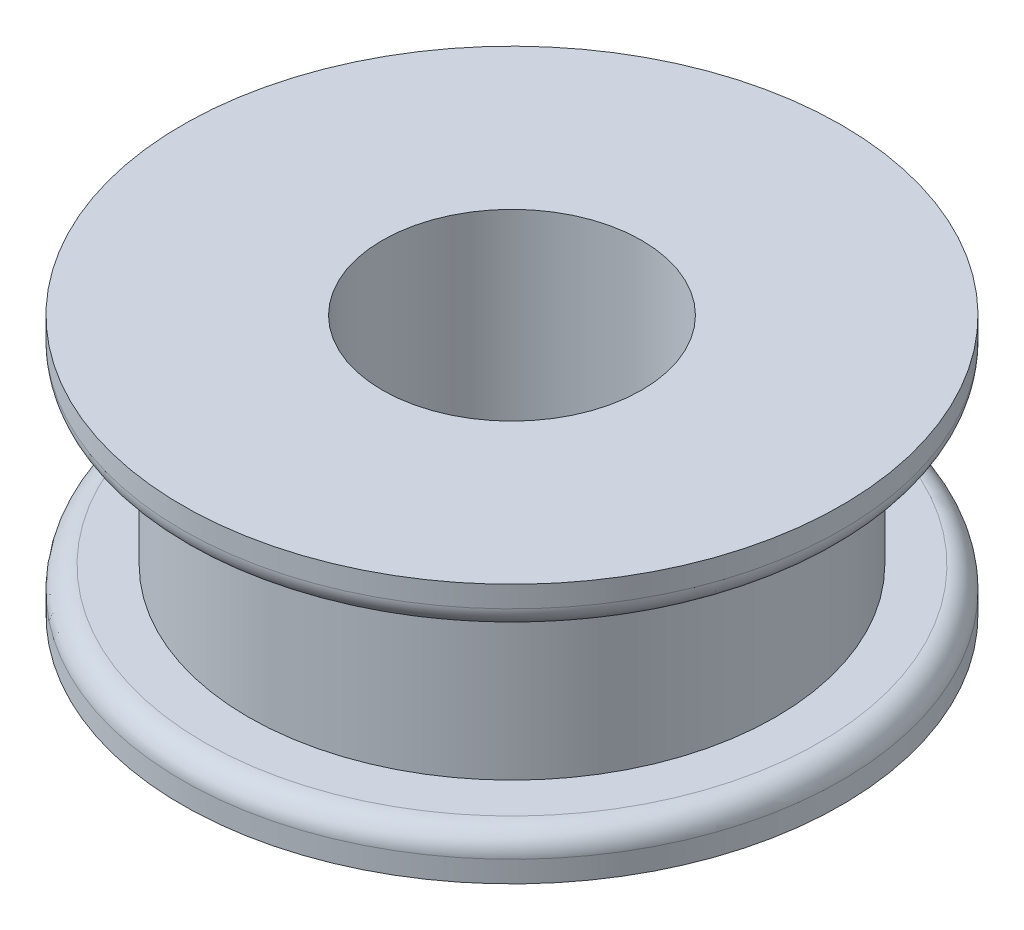
SolidWorks part; units mm, degrees
material "6061-T6 (SS)"
ref_plane "Front Plane" through (0, 0, 0) normal (1, 0, 0) x (0, 1, 0)
ref_plane "Top Plane" through (0, 0, 0) normal (0, 0, 1) x (0, 1, 0)
ref_plane "Right Plane" through (0, 0, 0) normal (0, 1, 0) x (-1, 0, 0)
sketch "Sketch1" plane through (0, 0, 0) normal (1, 0, 0) x (0, 1, 0)
  line L0 (-39.0416, 0) -> (31.6415, 0) construction
  line L1 (0, 3) -> (-6, 3)
  line L2 (-6, 3) -> (-6, 7.62)
  line L3 (-6, 7.62) -> (-5, 7.62)
  line L4 (-5, 7.62) -> (-5, 6.096)
  line L5 (-5, 6.096) -> (-1, 6.096)
  line L6 (-1, 6.096) -> (-1, 7.62)
  line L7 (-1, 7.62) -> (0, 7.62)
  line L8 (0, 7.62) -> (0, 3)
  dimension "D1" = 3
  dimension "D2" = 6.096
  dimension "D4" = 1.524
  dimension "D5" = 4
  dimension "D6" = 1
  dimension "D7" = 1
revolve "Revolve1" add sketch "Sketch1" angle 360 about L0
fillet "Fillet1" radius 0.508 2 edges at (0, -5, -7.62) (0, -1, -7.62)
equation "\"D1@Sketch1\"=3mm"
equation "\"D5@Sketch1\"=4mm"
equation "\"D6@Sketch1\"=1mm"
equation "\"D7@Sketch1\"=1mm"
